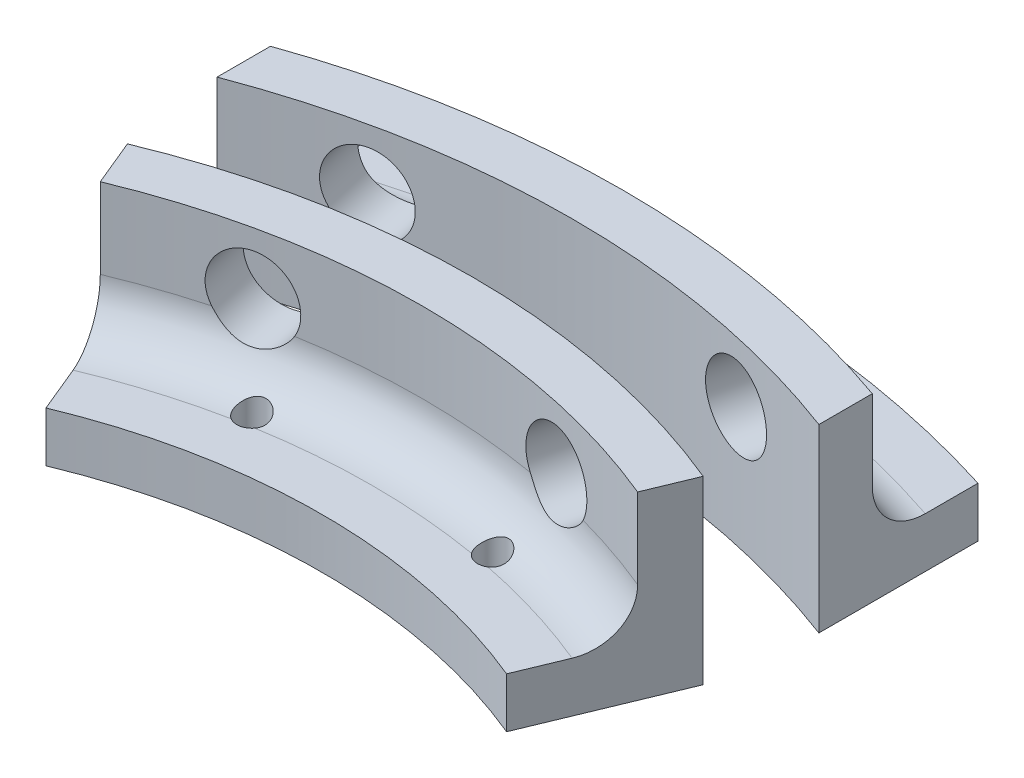
SolidWorks part; units mm, degrees
ref_plane "Front Plane" through (0, 0, 0) normal (0, 0, 1) x (1, 0, 0)
ref_plane "Top Plane" through (0, 0, 0) normal (0, 1, 0) x (1, 0, 0)
ref_plane "Right Plane" through (0, 0, 0) normal (1, 0, 0) x (0, 0, -1)
sketch "Sketch1" plane through (0, 0, 0) normal (0, 1, 0) x (1, 0, 0)
  line L0 (-22.961, 55.4328) -> (-28.7013, 69.291)
  line L1 (0, 0) -> (0, 100) construction
  line L2 (22.961, 55.4328) -> (28.7013, 69.291)
  line L3 (-32.5281, 78.5298) -> (-38.2683, 92.388)
  line L4 (32.5281, 78.5298) -> (38.2683, 92.388)
  arc A1 (22.961, 55.4328) -> (-22.961, 55.4328) centre (0, 0) ccw
  arc A2 (38.2683, 92.388) -> (-38.2683, 92.388) centre (0, 0) ccw
  arc A3 (28.7013, 69.291) -> (-28.7013, 69.291) centre (0, 0) ccw
  arc A4 (32.5281, 78.5298) -> (-32.5281, 78.5298) centre (0, 0) ccw
  dimension "D2" = 200
  dimension "D3" = 120
  dimension "D5" = 150
  dimension "D6" = 170
  dimension "D4" = 45
extrude "Boss-Extrude1" add sketch "Sketch1" along normal blind 18
sketch "Sketch2" plane through (0, 18, 0) normal (0, 1, 0) x (1, 0, 0)
  line L0 (-22.961, 55.4328) -> (-26.7878, 64.6716)
  line L1 (22.961, 55.4328) -> (26.7878, 64.6716)
  line L2 (-38.2683, 92.388) -> (-32.5281, 78.5298) construction
  line L3 (32.5281, 78.5298) -> (38.2683, 92.388) construction
  line L4 (-34.4415, 83.1492) -> (-40.1818, 97.0074)
  line L5 (34.4415, 83.1492) -> (40.1818, 97.0074)
  arc A0 (34.4415, 83.1492) -> (-34.4415, 83.1492) centre (0, 0) ccw
  arc A1 (40.1818, 97.0074) -> (-40.1818, 97.0074) centre (0, 0) ccw
  arc A2 (26.7878, 64.6716) -> (-26.7878, 64.6716) centre (0, 0) ccw
  arc A3 (22.961, 55.4328) -> (-22.961, 55.4328) centre (0, 0) ccw
  arc A4 (28.7013, 69.291) -> (-28.7013, 69.291) centre (0, 0) ccw construction
  arc A5 (32.5281, 78.5298) -> (-32.5281, 78.5298) centre (0, 0) ccw construction
  dimension "D1" = 5
  dimension "D2" = 5
  dimension "D3" = 15
extrude "Cut-Extrude1" cut sketch "Sketch2" against normal blind 13
fillet "Fillet1" radius 5 1 edges at (0, 5, -90)
fillet "Fillet2" radius 5 1 edges at (0, 5, -70)
sketch "Sketch3" plane through (0, 5, 0) normal (0, 1, 0) x (1, 0, 0)
  line L0 (0, 100) -> (0, 0) construction
  line L1 (-21.644, 97.6296) -> (0, 0)
  line L2 (21.644, 97.6296) -> (0, 0)
  arc A0 (38.2683, 92.388) -> (-38.2683, 92.388) centre (0, 0) ccw construction
  arc A1 (17.3152, 78.1037) -> (-17.3152, 78.1037) centre (0, 0) ccw
  dimension "D2" = 160
  dimension "D1" = 25
ref_plane "Plane1" through (-21.644, 0, -97.6296) normal (-0.2164, 0, -0.9763) x (-0.9763, 0, 0.2164)
sketch "Sketch4" plane through (-21.644, 0, -97.6296) normal (-0.2164, 0, -0.9763) x (-0.9763, 0, 0.2164)
  line L0 (0, 0) -> (0, 12)
  circle A0 centre (0, 12) radius 4
  dimension "D2" = 8
  dimension "D1" = 12
extrude "Cut-Extrude2" cut sketch "Sketch4" against normal through all both and the other way through all
mirror "Mirror1" about plane through (0, 0, 0) normal (1, 0, 0) of "Cut-Extrude2"
sketch "Sketch5" plane through (0, 5, 0) normal (0, 1, 0) x (1, 0, 0)
  line L0 (0, 100) -> (0, 0) construction
  line L2 (12, 95) -> (-12, 95)
  line L3 (12, 95) -> (12, 65)
  line L4 (12, 65) -> (-12, 65)
  line L5 (-12, 95) -> (-12, 65)
  line L6 (12, 95) -> (-12, 65) construction
  line L7 (12, 65) -> (-12, 95) construction
  arc A0 (17.3152, 78.1037) -> (-17.3152, 78.1037) centre (0, 0) ccw construction
  circle A1 centre (12, 95) radius 1.5
  circle A2 centre (-12, 95) radius 1.5
  circle A3 centre (-12, 65) radius 1.5
  circle A4 centre (12, 65) radius 1.5
  point P0 (0, 80)
  point P8 (0, 80)
  arc M4 (24.8744, 60.0522) -> (-24.8744, 60.0522) centre (0, 0) ccw
  dimension "D3" = 3
  dimension "D4" = 3
  dimension "D5" = 3
  dimension "D6" = 3
  dimension "D1" = 24
  dimension "D2" = 30
extrude "Cut-Extrude3" cut sketch "Sketch5" against normal through all both and the other way through all contours L5 A2 L2 | L2 A2 L5 | L3 A1 L2 | L2 A1 L3 | A3 L4 L5 M4 | A3 M4 | L4 A3 L5 | A4 M4 | A4 L3 L4 M4 | L3 A4 L4
sketch "Sketch6" plane through (0, 0, 0) normal (0, -1, 0) x (1, 0, 0)
  line L0 (0, 0) -> (0, -100) construction
  line L2 (-30, 0) -> (-30, -180)
  line L4 (30, 0) -> (30, -180)
  line L5 (-30, 0) -> (-50, 0)
  line L6 (-50, 0) -> (-50, -180)
  line L7 (-50, -180) -> (-30, -180)
  line L8 (50, -180) -> (30, -180)
  line L9 (50, 0) -> (50, -180)
  line L10 (30, 0) -> (50, 0)
  arc A0 (-38.2683, -92.388) -> (38.2683, -92.388) centre (0, 0) ccw construction
  point P14 (-50, -97.4758)
  dimension "D1" = 60
  dimension "D2" = 20
  dimension "D3" = 180
extrude "Cut-Extrude4" cut sketch "Sketch6" against normal through all both and the other way through all
